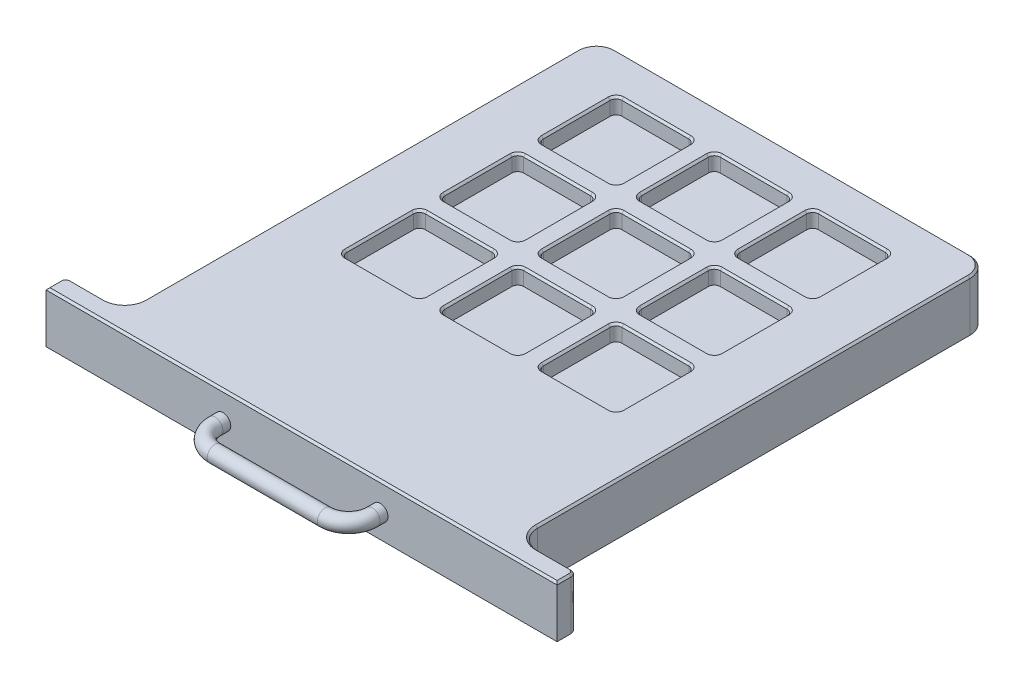
SolidWorks part; units mm, degrees
material "1060 合金"
ref_plane "前视基准面" through (0, 0, 0) normal (0, 0, 1) x (1, 0, 0)
ref_plane "上视基准面" through (0, 0, 0) normal (0, 1, 0) x (1, 0, 0)
ref_plane "右视基准面" through (0, 0, 0) normal (1, 0, 0) x (0, 0, -1)
sketch "草图1" plane through (0, 0, 0) normal (0, 1, 0) x (1, 0, 0)
  line L0 (0, -323.2072) -> (0, 393.6425) construction
  line L1 (-90, 250) -> (90, 250)
  line L2 (100, 240) -> (100, 20)
  line L3 (110, 10) -> (127, 10)
  line L4 (130, 7) -> (130, 0)
  line L5 (130, 0) -> (-130, 0)
  line L6 (-130, 7) -> (-130, 0)
  line L7 (-110, 10) -> (-127, 10)
  line L8 (-100, 240) -> (-100, 20)
  arc A0 (110, 10) -> (100, 20) centre (110, 20) cw
  arc A1 (100, 240) -> (90, 250) centre (90, 240) ccw
  arc A2 (130, 7) -> (127, 10) centre (127, 7) ccw
  arc A3 (-130, 7) -> (-127, 10) centre (-127, 7) cw
  arc A4 (-100, 240) -> (-90, 250) centre (-90, 240) cw
  arc A5 (-110, 10) -> (-100, 20) centre (-110, 20) ccw
  point P3 (-130, 10)
  point P9 (0, 250)
  point P13 (100, 250)
  point P16 (130, 10)
  point P27 (0, 0)
  point P28 (-100, 250)
  dimension "D5" = 10
  dimension "D6" = 3
  dimension "D1" = 250
  dimension "D2" = 130
  dimension "D3" = 100
  dimension "D4" = 10
extrude "凸台-拉伸1" add sketch "草图1" along normal blind 26
sketch "草图3" plane through (0, 26, 0) normal (0, 1, 0) x (1, 0, 0)
  line L0 (0, 250) -> (0, 0) construction
  line L1 (90, 250) -> (-90, 250) construction
  line L2 (-130, 0) -> (130, 0) construction
  line L3 (-70, 90) -> (70, 90) construction
  line L4 (-70, 90) -> (-70, 230) construction
  line L5 (-70, 230) -> (70, 230) construction
  line L6 (70, 90) -> (70, 230) construction
  line L7 (-70, 90) -> (70, 230) construction
  line L8 (-70, 230) -> (70, 90) construction
  line L10 (-67, 230) -> (-33, 230)
  line L11 (-70, 227) -> (-70, 193)
  line L12 (-67, 190) -> (-33, 190)
  line L13 (-30, 227) -> (-30, 193)
  arc A0 (-30, 193) -> (-33, 190) centre (-33, 193) cw
  arc A1 (-67, 190) -> (-70, 193) centre (-67, 193) cw
  arc A2 (-30, 227) -> (-33, 230) centre (-33, 227) ccw
  arc A3 (-67, 230) -> (-70, 227) centre (-67, 227) ccw
  point P5 (0, 160)
  point P19 (-70, 190)
  point P22 (-30, 230)
  dimension "D6" = 3
  dimension "D1" = 160
  dimension "D2" = 140
  dimension "D3" = 140
  dimension "D4" = 40
  dimension "D5" = 40
extrude "切除-拉伸3" cut sketch "草图3" against normal blind 8
pattern_linear "阵列(线性)3" count 3 spacing 50 along (1, 0, 0) count 3 spacing 50 along (0, 0, 1) of "切除-拉伸3"
chamfer "倒角3" distance 1 angle 45 86 edges at (70, 26, -110) (69.1213, 26, -129.1213) (50, 26, -130) (30.8787, 26, -129.1213) (30, 26, -110) (30.8787, 26, -90.8787) (50, 26, -90) (69.1213, 26, -90.8787) (20, 26, -110) (19.1213, 26, -129.1213) (0, 26, -130) (-19.1213, 26, -129.1213) (-20, 26, -110) (-19.1213, 26, -90.8787) (0, 26, -90) (19.1213, 26, -90.8787) (-30, 26, -110) (-30.8787, 26, -129.1213) (-50, 26, -130) (-69.1213, 26, -129.1213) (-70, 26, -110) (-69.1213, 26, -90.8787) (-50, 26, -90) (-30.8787, 26, -90.8787) (70, 26, -160) (69.1213, 26, -179.1213) (50, 26, -180) (30.8787, 26, -179.1213) (30, 26, -160) (30.8787, 26, -140.8787) (50, 26, -140) (69.1213, 26, -140.8787) (20, 26, -160) (19.1213, 26, -179.1213) (0, 26, -180) (-19.1213, 26, -179.1213) (-20, 26, -160) (-19.1213, 26, -140.8787) (0, 26, -140) (19.1213, 26, -140.8787) (-30, 26, -160) (-30.8787, 26, -179.1213) (-50, 26, -180) (-69.1213, 26, -179.1213) (-70, 26, -160) (-69.1213, 26, -140.8787) (-50, 26, -140) (-30.8787, 26, -140.8787) (70, 26, -210) (69.1213, 26, -229.1213) (50, 26, -230) (30.8787, 26, -229.1213) (30, 26, -210) (30.8787, 26, -190.8787) (50, 26, -190) (69.1213, 26, -190.8787) (118.5, 26, -10) (129.1213, 26, -9.1213) (130, 26, -3.5) (0, 26, 0) (-130, 26, -3.5) (-129.1213, 26, -9.1213) (-118.5, 26, -10) (-102.9289, 26, -12.9289) (-100, 26, -130) (-97.0711, 26, -247.0711) (0, 26, -250) (97.0711, 26, -247.0711) (100, 26, -130) (102.9289, 26, -12.9289) (-30.8787, 26, -229.1213) (-50, 26, -230) (-69.1213, 26, -229.1213) (-70, 26, -210) (-69.1213, 26, -190.8787) (-50, 26, -190) (-30.8787, 26, -190.8787) (-30, 26, -210) (19.1213, 26, -229.1213) (0, 26, -230) (-19.1213, 26, -229.1213) (-20, 26, -210) (-19.1213, 26, -190.8787) (0, 26, -190) (19.1213, 26, -190.8787) (20, 26, -210)
ref_plane "基准面1" through (0, 12, 0) normal (0, -1, 0) x (-1, 0, 0)
sketch "草图4" plane through (0, 12, 0) normal (0, -1, 0) x (-1, 0, 0)
  line L0 (0, 0) -> (0, -14.2627) construction
  line L1 (-40, 0) -> (-40, -4)
  line L2 (130, 0) -> (-130, 0) construction
  line L3 (-28, -16) -> (28, -16)
  line L4 (40, 0) -> (40, -4)
  arc A0 (-28, -16) -> (-40, -4) centre (-28, -4) cw
  arc A1 (28, -16) -> (40, -4) centre (28, -4) ccw
  point P8 (40, -16)
  point P10 (-40, -16)
  point P15 (0, -16)
  dimension "D3" = 12
  dimension "D1" = 40
  dimension "D2" = 16
sketch "草图5" plane through (0, 0, 0) normal (0, 0, 1) x (1, 0, 0)
  circle A0 centre (-40, 12) radius 4
  dimension "D1" = 8
sweep "扫描1" add profiles "草图5" path "草图4"
